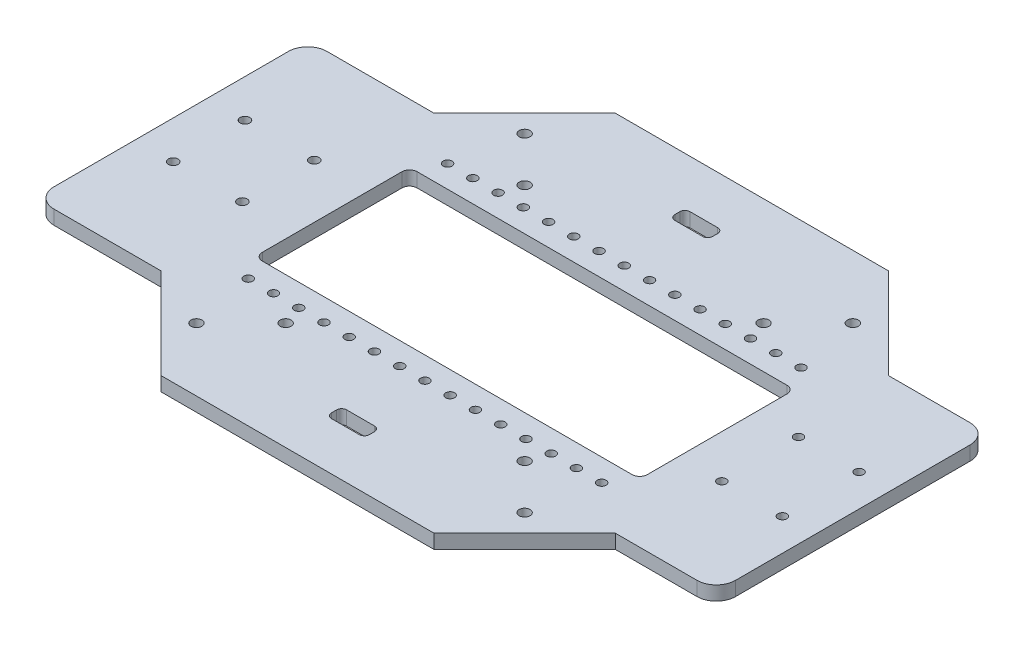
SolidWorks part; units mm, degrees
ref_plane "Front Plane" through (0, 0, 0) normal (0, 0, 1) x (1, 0, 0)
ref_plane "Top Plane" through (0, 0, 0) normal (0, 1, 0) x (1, 0, 0)
ref_plane "Right Plane" through (0, 0, 0) normal (1, 0, 0) x (0, 0, -1)
sketch "Sketch1" plane through (0, 0, 0) normal (0, 1, 0) x (1, 0, 0)
  line L0 (-73.2542, 28.5227) -> (-37.3332, 64.4437)
  line L1 (-37.3332, 64.4437) -> (70.8248, 64.4437)
  line L2 (70.8248, 64.4437) -> (106.7458, 28.5227)
  line L3 (106.7458, 28.5227) -> (106.7458, -79.6353)
  line L4 (106.7458, -79.6353) -> (70.8248, -115.5563)
  line L5 (70.8248, -115.5563) -> (-37.3332, -115.5563)
  line L6 (-37.3332, -115.5563) -> (-73.2542, -79.6353)
  line L7 (-73.2542, -79.6353) -> (-73.2542, 28.5227)
  dimension "D1" = 180
  dimension "D2" = 50.8
  dimension "D3" = 180
extrude "Boss-Extrude1" add sketch "Sketch1" along normal blind 5.588
sketch "Sketch2" plane through (0, 5.588, 0) normal (0, 1, 0) x (1, 0, 0)
  line L0 (-48.2542, 39.4437) -> (81.7458, 39.4437) construction
  line L1 (81.7458, 39.4437) -> (81.7458, -90.5563) construction
  line L2 (81.7458, -90.5563) -> (-48.2542, -90.5563) construction
  line L3 (-48.2542, -90.5563) -> (-48.2542, 39.4437) construction
  line L4 (-30.5765, 21.766) -> (64.0681, 21.766) construction
  line L5 (64.0681, 21.766) -> (64.0681, -72.8786) construction
  line L6 (64.0681, -72.8786) -> (-30.5765, -72.8786) construction
  line L7 (-30.5765, -72.8786) -> (-30.5765, 21.766) construction
  line L8 (-48.2542, 39.4437) -> (-30.5765, 21.766) construction
  line L9 (64.0681, 21.766) -> (81.7458, 39.4437) construction
  line L10 (-48.2542, -90.5563) -> (-30.5765, -72.8786) construction
  line L11 (64.0681, -72.8786) -> (81.7458, -90.5563) construction
  line L12 (-73.2542, -25.5563) -> (-48.2542, -25.5563) construction
  line L13 (-73.2542, 28.5227) -> (-73.2542, -79.6353) construction
  line L14 (16.7458, 39.4437) -> (16.7458, 64.4437) construction
  line L15 (70.8248, 64.4437) -> (-37.3332, 64.4437) construction
  line L19 (81.7458, -25.5563) -> (106.7458, -25.5563) construction
  line L20 (106.7458, -79.6353) -> (106.7458, 28.5227) construction
  line L21 (16.7458, -90.5563) -> (16.7458, -115.5563) construction
  line L22 (-37.3332, -115.5563) -> (70.8248, -115.5563) construction
  circle A0 centre (-48.2542, 39.4437) radius 2.159
  circle A1 centre (-30.5765, 21.766) radius 2.159
  circle A2 centre (-48.2542, -90.5563) radius 2.159
  circle A3 centre (-30.5765, -72.8786) radius 2.159
  circle A4 centre (64.0681, 21.766) radius 2.159
  circle A5 centre (81.7458, 39.4437) radius 2.159
  circle A6 centre (64.0681, -72.8786) radius 2.159
  circle A7 centre (81.7458, -90.5563) radius 2.159
  dimension "D1" = 4.318
  dimension "D2" = 25
  dimension "D3" = 130
  dimension "D4" = 94.6447
extrude "Cut-Extrude1" cut sketch "Sketch2" against normal through all
sketch "Sketch3" plane through (0, 5.588, 0) normal (0, 1, 0) x (1, 0, 0)
  line L5 (-59.5092, 5.1137) -> (93.0008, 5.1137)
  line L6 (-59.5092, 5.1137) -> (-59.5092, -56.2263)
  line L7 (-59.5092, -56.2263) -> (93.0008, -56.2263)
  line L12 (93.0008, 5.1137) -> (93.0008, -56.2263)
  line L16 (-73.2542, -25.5563) -> (106.7458, -25.5563) construction
  line L17 (-73.2542, 28.5227) -> (-73.2542, -79.6353) construction
  line L18 (106.7458, -79.6353) -> (106.7458, 28.5227) construction
  line L19 (16.7458, -115.5563) -> (16.7458, 64.4437) construction
  line L20 (-37.3332, -115.5563) -> (70.8248, -115.5563) construction
  line L21 (70.8248, 64.4437) -> (-37.3332, 64.4437) construction
  dimension "D2" = 152.51
  dimension "D4" = 61.34
extrude "Cut-Extrude2" cut sketch "Sketch3" against normal through all
sketch "Sketch5" plane through (0, 5.588, 0) normal (0, 1, 0) x (1, 0, 0)
  line L1 (-73.2542, -79.6353) -> (-115.6342, -79.6353)
  line L2 (-73.2542, -79.6353) -> (-73.2542, 28.5227)
  line L3 (-73.2542, 28.5227) -> (-115.6342, 28.5227)
  line L4 (-123.2542, -72.0153) -> (-123.2542, 20.9027)
  arc A0 (-115.6342, -79.6353) -> (-123.2542, -72.0153) centre (-115.6342, -72.0153) cw
  arc A1 (-123.2542, 20.9027) -> (-115.6342, 28.5227) centre (-115.6342, 20.9027) cw
  point P10 (-123.2542, 28.5227)
  dimension "D2" = 7.62
  dimension "D1" = 50
extrude "Boss-Extrude2" add sketch "Sketch5" against normal up to surface (5.588 mm away) up to face at (16.7458, 0, 25.5563)
sketch "Sketch6" plane through (0, 5.588, 0) normal (0, 1, 0) x (1, 0, 0)
  line L1 (106.7458, 28.5227) -> (139.1258, 28.5227)
  line L2 (106.7458, 28.5227) -> (106.7458, -79.6353)
  line L3 (106.7458, -79.6353) -> (139.1258, -79.6353)
  line L4 (146.7458, 20.9027) -> (146.7458, -72.0153)
  arc A0 (139.1258, 28.5227) -> (146.7458, 20.9027) centre (139.1258, 20.9027) cw
  arc A1 (146.7458, -72.0153) -> (139.1258, -79.6353) centre (139.1258, -72.0153) cw
  point P8 (146.7458, 28.5227)
  dimension "D2" = 7.62
  dimension "D1" = 40
extrude "Boss-Extrude3" add sketch "Sketch6" against normal up to surface (5.588 mm away) up to face at (16.7458, 0, 25.5563)
sketch "Sketch7" plane through (0, 5.588, 0) normal (0, 1, 0) x (1, 0, 0)
  line L0 (110.0458, -40.7563) -> (110.0458, -10.3563) construction
  line L1 (110.0458, -10.3563) -> (134.0458, -10.3563) construction
  line L2 (134.0458, -10.3563) -> (134.0458, -40.7563) construction
  line L3 (134.0458, -40.7563) -> (110.0458, -40.7563) construction
  line L4 (-123.2542, -25.5563) -> (146.7458, -25.5563) construction
  line L5 (-123.2542, 20.9027) -> (-123.2542, -72.0153) construction
  line L6 (146.7458, -72.0153) -> (146.7458, 20.9027) construction
  circle A0 centre (110.0458, -10.3563) radius 1.75
  circle A1 centre (134.0458, -10.3563) radius 1.75
  circle A2 centre (110.0458, -40.7563) radius 1.75
  circle A3 centre (134.0458, -40.7563) radius 1.75
  dimension "D3" = 3.5
  dimension "D1" = 24
  dimension "D2" = 30.4
  dimension "D4" = 12.7
extrude "Cut-Extrude4" cut sketch "Sketch7" against normal through all
sketch "Sketch9" plane through (0, 5.588, 0) normal (0, 1, 0) x (1, 0, 0)
  line L2 (16.7458, 64.4437) -> (16.7458, -115.5563) construction
  line L3 (70.8248, 64.4437) -> (-37.3332, 64.4437) construction
  line L4 (-37.3332, -115.5563) -> (70.8248, -115.5563) construction
  line L5 (93.0008, 5.1137) -> (-59.5092, 5.1137) construction
  line L6 (-123.2542, -25.5563) -> (146.7458, -25.5563) construction
  line L7 (-123.2542, 20.9027) -> (-123.2542, -72.0153) construction
  line L8 (146.7458, -72.0153) -> (146.7458, 20.9027) construction
  circle A0 centre (-53.2542, 13.9237) radius 1.75
  circle A1 centre (-43.2542, 13.9237) radius 1.75
  circle A2 centre (-33.2542, 13.9237) radius 1.75
  circle A3 centre (-23.2542, 13.9237) radius 1.75
  circle A4 centre (-13.2542, 13.9237) radius 1.75
  circle A5 centre (-3.2542, 13.9237) radius 1.75
  circle A6 centre (6.7458, 13.9237) radius 1.75
  circle A7 centre (16.7458, 13.9237) radius 1.75
  circle A8 centre (26.7458, 13.9237) radius 1.75
  circle A9 centre (36.7458, 13.9237) radius 1.75
  circle A10 centre (46.7458, 13.9237) radius 1.75
  circle A11 centre (56.7458, 13.9237) radius 1.75
  circle A12 centre (66.7458, 13.9237) radius 1.75
  circle A13 centre (76.7458, 13.9237) radius 1.75
  circle A14 centre (86.7458, 13.9237) radius 1.75
  circle A15 centre (-53.2542, -65.0363) radius 1.75
  circle A16 centre (-43.2542, -65.0363) radius 1.75
  circle A17 centre (-33.2542, -65.0363) radius 1.75
  circle A18 centre (-23.2542, -65.0363) radius 1.75
  circle A19 centre (-13.2542, -65.0363) radius 1.75
  circle A20 centre (-3.2542, -65.0363) radius 1.75
  circle A21 centre (6.7458, -65.0363) radius 1.75
  circle A22 centre (16.7458, -65.0363) radius 1.75
  circle A23 centre (26.7458, -65.0363) radius 1.75
  circle A24 centre (36.7458, -65.0363) radius 1.75
  circle A25 centre (46.7458, -65.0363) radius 1.75
  circle A26 centre (56.7458, -65.0363) radius 1.75
  circle A27 centre (66.7458, -65.0363) radius 1.75
  circle A28 centre (76.7458, -65.0363) radius 1.75
  circle A29 centre (86.7458, -65.0363) radius 1.75
  dimension "D1" = 3.5
  dimension "D4" = 3.5
  dimension "D3" = 8.81
  dimension "D6" = 78.96
  dimension "D7" = 140
  dimension "D8" = 10
  dimension "D2" = 15
  dimension "D5" = 15
extrude "Cut-Extrude8" cut sketch "Sketch9" against normal through all
sketch "Sketch10" plane through (0, 5.588, 0) normal (0, 1, 0) x (1, 0, 0)
  line L0 (-123.2542, -25.5563) -> (146.7458, -25.5563) construction
  line L1 (11.2458, 45.4437) -> (22.2458, 45.4437)
  line L2 (9.2458, 43.4437) -> (9.2458, 41.4437)
  line L3 (11.2458, 39.4437) -> (22.2458, 39.4437)
  line L4 (24.2458, 43.4437) -> (24.2458, 41.4437)
  line L5 (11.2458, -90.5563) -> (22.2458, -90.5563)
  line L6 (9.2458, -92.5563) -> (9.2458, -94.5563)
  line L7 (11.2458, -96.5563) -> (22.2458, -96.5563)
  line L8 (24.2458, -92.5563) -> (24.2458, -94.5563)
  line L9 (-123.2542, 20.9027) -> (-123.2542, -72.0153) construction
  line L10 (146.7458, -72.0153) -> (146.7458, 20.9027) construction
  line L11 (16.7458, -115.5563) -> (16.7458, 64.4437) construction
  line L12 (-37.3332, -115.5563) -> (70.8248, -115.5563) construction
  line L13 (70.8248, 64.4437) -> (-37.3332, 64.4437) construction
  arc A0 (9.2458, -94.5563) -> (11.2458, -96.5563) centre (11.2458, -94.5563) ccw
  arc A1 (22.2458, -96.5563) -> (24.2458, -94.5563) centre (22.2458, -94.5563) ccw
  arc A2 (24.2458, -92.5563) -> (22.2458, -90.5563) centre (22.2458, -92.5563) ccw
  arc A3 (11.2458, -90.5563) -> (9.2458, -92.5563) centre (11.2458, -92.5563) ccw
  arc A4 (9.2458, 41.4437) -> (11.2458, 39.4437) centre (11.2458, 41.4437) ccw
  arc A5 (22.2458, 39.4437) -> (24.2458, 41.4437) centre (22.2458, 41.4437) ccw
  arc A6 (24.2458, 43.4437) -> (22.2458, 45.4437) centre (22.2458, 43.4437) ccw
  arc A7 (11.2458, 45.4437) -> (9.2458, 43.4437) centre (11.2458, 43.4437) ccw
  point P32 (24.2458, 39.4437)
  point P35 (24.2458, 45.4437)
  point P38 (9.2458, 45.4437)
  dimension "D4" = 2
  dimension "D1" = 15
  dimension "D2" = 6
  dimension "D3" = 65
extrude "Cut-Extrude9" cut sketch "Sketch10" against normal through all
fillet "Fillet1" radius 3 4 edges at (-59.5092, 2.794, 56.2263) (93.0008, 2.794, 56.2263) (93.0008, 2.794, -5.1137) (-59.5092, 2.794, -5.1137)
sketch "Sketch11" plane through (0, 5.588, 0) normal (0, 1, 0) x (1, 0, 0)
  line L0 (-108.2542, -11.3323) -> (-80.8222, -11.3323) construction
  line L1 (-80.8222, -11.3323) -> (-80.8222, -39.7803) construction
  line L2 (-80.8222, -39.7803) -> (-108.2542, -39.7803) construction
  line L3 (-108.2542, -39.7803) -> (-108.2542, -11.3323) construction
  line L4 (-123.2542, -25.5563) -> (-59.5092, -25.5563) construction
  line L5 (-123.2542, 20.9027) -> (-123.2542, -72.0153) construction
  line L6 (-59.5092, 2.1137) -> (-59.5092, -53.2263) construction
  circle A0 centre (-108.2542, -11.3323) radius 1.905
  circle A1 centre (-80.8222, -11.3323) radius 1.905
  circle A2 centre (-80.8222, -39.7803) radius 1.905
  circle A3 centre (-108.2542, -39.7803) radius 1.905
  dimension "D1" = 3.81
  dimension "D2" = 27.432
  dimension "D3" = 28.448
  dimension "D4" = 15
extrude "Cut-Extrude10" cut sketch "Sketch11" against normal through all
